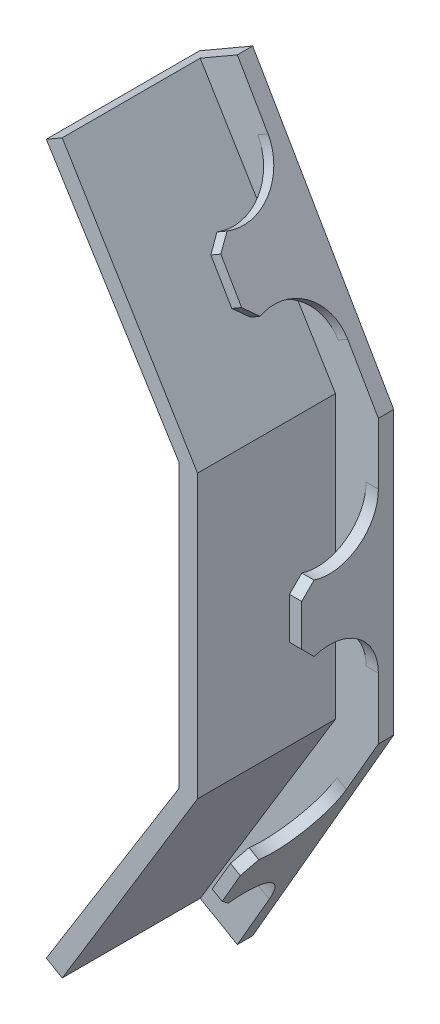
SolidWorks part; units mm, degrees
ref_plane "Front Plane" through (0, 0, 0) normal (1, 0, 0) x (0, 1, 0)
ref_plane "Top Plane" through (0, 0, 0) normal (0, 0, 1) x (0, 1, 0)
ref_plane "Right Plane" through (0, 0, 0) normal (0, 1, 0) x (-1, 0, 0)
sketch "Sketch1" plane through (0, 0, 0) normal (0, 0, 1) x (0, 1, 0)
  line L0 (0, 0) -> (46, 0)
  line L1 (46, 0) -> (85.8372, 23)
  line L2 (-39.8372, 23) -> (-34.8372, 31.6603)
  line L3 (0, 0) -> (-39.8372, 23)
  line L7 (85.8372, 23) -> (80.8372, 31.6603)
  line L9 (0, 10) -> (46, 10)
  line L10 (46, 10) -> (80.8372, 31.6603)
  line L11 (0, 10) -> (-34.8372, 31.6603)
extrude "Boss-Extrude2" add sketch "Sketch1" along normal blind 25 contours L2 L11 L9 L10 L7 L1 L0 L3
sketch "Sketch5" plane through (0, 0, 25) normal (0, 0, 1) x (1, 0, 0)
  line L0 (-24.7321, -38.8372) -> (-29.0622, -36.3372)
  line L3 (-23, -39.8372) -> (-31.6603, -34.8372) construction
  line L4 (-24.7321, -38.8372) -> (-2, 0)
  line L5 (-7, 0) -> (-29.0622, -36.3372)
  line L6 (-7, 0) -> (-7, 46)
  line L9 (-24.7321, 84.8372) -> (-29.0622, 82.3372)
  line L10 (-24.7321, 84.8372) -> (-2, 46)
  line L11 (-7, 46) -> (-29.0622, 82.3372)
  line L12 (-2, 0) -> (-2, 46)
  point P16 (-2, 23)
  point P20 (-7, 23)
extrude "Cut-Extrude4" cut sketch "Sketch5" against normal blind 22.5
sketch "Sketch6" plane through (0, 0, 0) normal (1, 0, 0) x (0, 1, 0)
  line L0 (0, 2.5) -> (10, 2.5)
  line L3 (0, 25) -> (0, 0) construction
  line L4 (0, 2.5) -> (0, 25)
  line L5 (0, 25) -> (46, 25)
  line L7 (46, 25) -> (46, 0) construction
  line L8 (46, 2.5) -> (46, 25)
  line L10 (36, 2.5) -> (46, 2.5)
  line L12 (19.6144, 15) -> (26.3856, 15)
  line L17 (17.6031, 12.9887) -> (19.6144, 15)
  line L20 (28.3969, 12.9887) -> (26.3856, 15)
  arc A2 (10, 2.5) -> (17.6031, 12.9887) centre (10, 10.5) ccw
  arc A3 (36, 2.5) -> (28.3969, 12.9887) centre (36, 10.5) cw
extrude "Cut-Extrude5" cut sketch "Sketch6" against normal blind 2
sketch "Sketch7" plane through (19.9186, 11.5, 0) normal (0.866, 0.5, 0) x (-0.5, 0.866, 0)
  line L0 (39.8372, 2.5) -> (39.8372, 25)
  line L1 (39.8372, 25) -> (85.8372, 25)
  line L2 (85.8372, 25) -> (85.8372, 2.5)
  line L3 (62.8372, 0) -> (62.8372, 15)
  line L4 (39.8372, 0) -> (85.8372, 0) construction
  line L5 (59.4515, 15) -> (66.2228, 15)
  line L6 (49.8372, 2.5) -> (39.8372, 2.5)
  line L7 (75.8372, 2.5) -> (85.8372, 2.5)
  line L12 (57.4402, 12.9887) -> (59.4515, 15)
  line L13 (68.2341, 12.9887) -> (66.2228, 15)
  arc A0 (49.8372, 2.5) -> (57.4402, 12.9887) centre (49.8372, 10.5) ccw
  arc A1 (75.8372, 2.5) -> (68.2341, 12.9887) centre (75.8372, 10.5) cw
  line M16 (85.8372, 0) -> (85.8372, 25)
  line M17 (85.8372, 25) -> (39.8372, 25)
  line M18 (39.8372, 25) -> (39.8372, 2.5)
extrude "Cut-Extrude6" cut sketch "Sketch7" against normal blind 2 contours A1 L7 L6 A0 L12 L5 L13 M16 M17 M18
sketch "Sketch8" plane through (0, 0, 0) normal (0.866, -0.5, 0) x (0.5, 0.866, 0)
  line L0 (0, 2.5) -> (0, 25)
  line L1 (0, 25) -> (-46, 25)
  line L2 (-46, 25) -> (-46, 2.5)
  line L3 (-46, 25) -> (-46, 0) construction
  line L4 (-23, 0) -> (-23, 15)
  line L5 (0, 0) -> (-46, 0) construction
  line L6 (-25.9614, 15) -> (-20.0386, 15)
  line L7 (-35.5758, 2.5) -> (-46, 2.5)
  line L8 (-10.4242, 2.5) -> (0, 2.5)
  line L13 (-27.9728, 12.9887) -> (-25.9614, 15)
  line L14 (-18.0272, 12.9887) -> (-20.0386, 15)
  arc A0 (-35.5758, 2.5) -> (-27.9728, 12.9887) centre (-35.5758, 10.5) ccw
  arc A1 (-10.4242, 2.5) -> (-18.0272, 12.9887) centre (-10.4242, 10.5) cw
  line M17 (0, 2.5) -> (0, 25)
  line M18 (0, 25) -> (-46, 25)
  line M19 (-46, 25) -> (-46, 0)
extrude "Cut-Extrude7" cut sketch "Sketch8" against normal blind 2 contours A1 L8 L7 A0 L13 L6 L14 M17 M18 M19
sketch "Sketch9" plane through (-10, 0, 0) normal (-1, 0, 0) x (0, -1, 0)
  circle A0 centre (-23, 12.5) radius 2.4
  circle A1 centre (-31, 12.5) radius 2.4
  circle A2 centre (-15, 12.5) radius 2.4
extrude "Boss-Extrude3" add sketch "Sketch9" along normal blind 10
